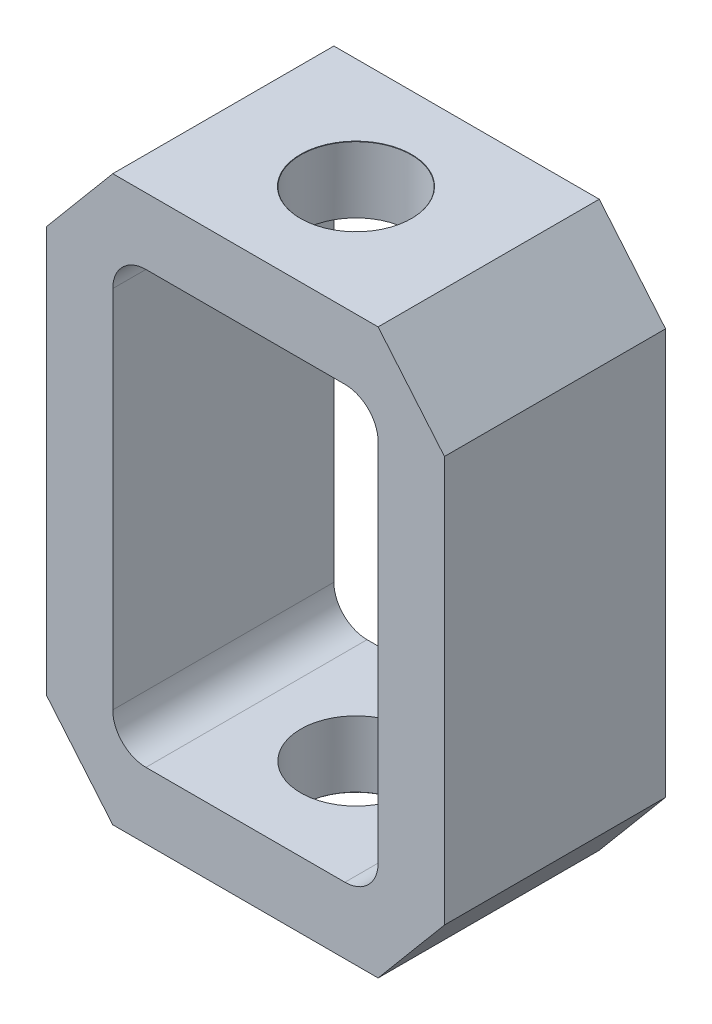
SolidWorks part; units mm, degrees
material "AISI 1045 Steel, cold drawn"
ref_plane "Front Plane" through (0, 0, 0) normal (0, 0, 1) x (1, 0, 0)
ref_plane "Top Plane" through (0, 0, 0) normal (0, 1, 0) x (1, 0, 0)
ref_plane "Right Plane" through (0, 0, 0) normal (1, 0, 0) x (0, 0, -1)
sketch "Sketch1" plane through (0, 0, 0) normal (0, 0, 1) x (1, 0, 0)
  line L0 (-12, -19.5) -> (-12, 19.5)
  line L5 (12, -19.5) -> (12, 19.5)
  line L6 (-12, 19.5) -> (12, 19.5)
  line L7 (0, 13.3234) -> (0, -8.3658) construction
  line L8 (-10.1474, 0) -> (11.2319, 0) construction
  line L9 (-18, -18.3495) -> (-18, 18.3495)
  line L10 (-18, 18.3495) -> (-12, 25.5)
  line L11 (-12, 25.5) -> (12, 25.5)
  line L12 (18, -18.3495) -> (18, 18.3495)
  line L13 (18, 18.3495) -> (12, 25.5)
  line L14 (18, -18.3495) -> (12, -25.5)
  line L15 (-12, -25.5) -> (12, -25.5)
  line L16 (-18, -18.3495) -> (-12, -25.5)
  line L17 (-12, -19.5) -> (12, -19.5)
  point P17 (0, 19.5)
  point P21 (0, 25.5)
  point P22 (18, 0)
  point P25 (-18, 0)
  point P26 (-12, 0)
  point P27 (12, 0)
  dimension "D1" = 25.5
  dimension "D2" = 6
  dimension "D3" = 6
  dimension "D4" = 24
  dimension "D6" = 220
extrude "Boss-Extrude1" add sketch "Sketch1" along normal mid plane 20 contours L9 L16 L15 L14 L12 L13 L11 L10 L17 L0 L6 L5
hole_wizard "Ø10.0mm Dowel Hole1" positions "3DSketch4" profile "Sketch6" hole size "Ø10.0" standard "ISO"
sketch3d "3DSketch4"
  line L1 (-12, 25.5, -10) -> (12, 25.5, -10) construction
  line L2 (-12, 25.5, 10) -> (-12, 25.5, -10) construction
  point P0 (0, 25.5, 0)
  point P9 (0, 25.5, -10)
  point P12 (-12, 25.5, 0)
sketch "Sketch6" plane through (0, 25.5, 0) normal (1, 0, 0) x (0, 0, 1)
  line L0 (0, 0) -> (0, 27.5043)
  line L1 (0, 27.5043) -> (5, 24.5)
  line L2 (5, 24.5) -> (5, 0.025)
  line L3 (5, 0.025) -> (5.025, 0)
  line L5 (5.025, 0) -> (0, 0)
  line L6 (-5, 0.025) -> (-5.025, 0) construction
  line L10 (0, 27.5043) -> (-5, 24.5) construction
  line L11 (0, -6.35) -> (0, 107.95) construction
  dimension "Hole Dia." = 10
  dimension "Hole Depth" = 24.5
  dimension "Near C'Sink Dia." = 10.05
  dimension "Near C'Sink Angle" = 90
  dimension "Drill Angle" = 118
hole_wizard "Ø10.0mm Dowel Hole2" positions "3DSketch5" profile "Sketch7" hole size "Ø10.0" standard "ISO"
sketch3d "3DSketch5"
  line L0 (-12, -25.5, 10) -> (-12, -25.5, -10) construction
  line L1 (-12, -25.5, -10) -> (12, -25.5, -10) construction
  point P0 (0, -25.5, 0)
  point P5 (-12, -25.5, 0)
  point P8 (0, -25.5, -10)
sketch "Sketch7" plane through (0, -25.5, 0) normal (1, 0, 0) x (0, 0, -1)
  line L0 (0, 0) -> (0, 27.5043)
  line L1 (0, 27.5043) -> (5, 24.5)
  line L2 (5, 24.5) -> (5, 0.025)
  line L3 (5, 0.025) -> (5.025, 0)
  line L5 (5.025, 0) -> (0, 0)
  line L6 (-5, 0.025) -> (-5.025, 0) construction
  line L10 (0, 27.5043) -> (-5, 24.5) construction
  line L11 (0, -6.35) -> (0, 107.95) construction
  dimension "Hole Dia." = 10
  dimension "Hole Depth" = 24.5
  dimension "Near C'Sink Dia." = 10.05
  dimension "Near C'Sink Angle" = 90
  dimension "Drill Angle" = 118
fillet "Fillet1" radius 3 4 edges at (-12, -19.5, 0) (12, -19.5, 0) (-12, 19.5, 0) (12, 19.5, 0)
